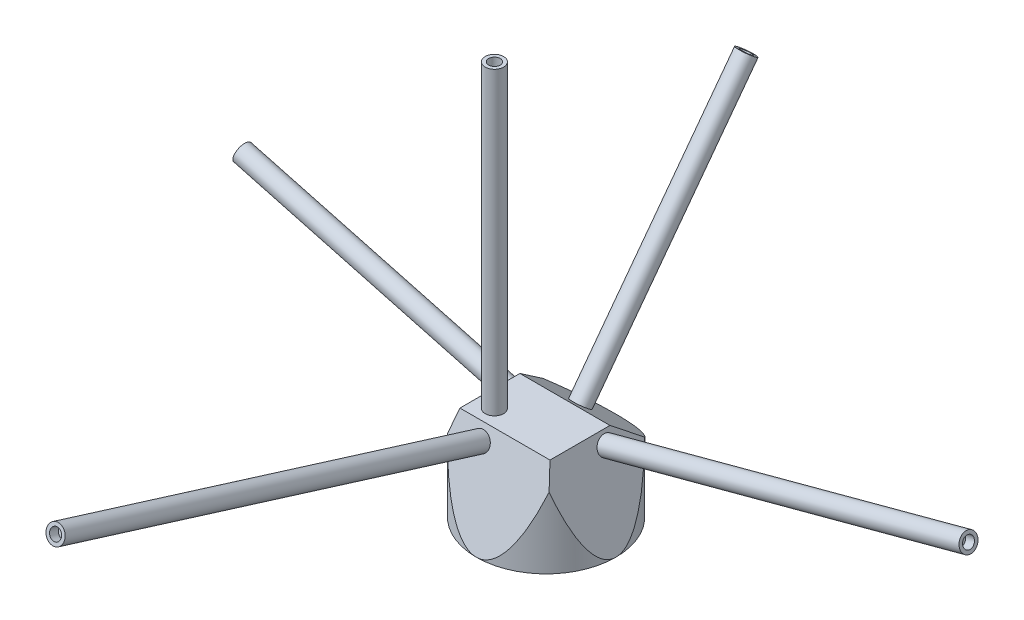
SolidWorks part; units mm, degrees
material "Ductile Iron"
ref_plane "Front Plane" through (0, 0, 0) normal (0, 0, 1) x (1, 0, 0)
ref_plane "Top Plane" through (0, 0, 0) normal (0, 1, 0) x (1, 0, 0)
ref_plane "Right Plane" through (0, 0, 0) normal (1, 0, 0) x (0, 0, -1)
sketch "Sketch1" plane through (0, 0, 0) normal (0, 1, 0) x (1, 0, 0)
  circle A0 centre (0, 0) radius 15.115
  dimension "D1" = 30.23
extrude "Boss-Extrude1" add sketch "Sketch1" against normal blind 20
ref_plane "Plane1" through (15.115, 0, 0) normal (1, 0, 0) x (0, 0, -1)
sketch "Sketch3" plane through (15.115, 0, 0) normal (1, 0, 0) x (0, 0, -1)
  line L0 (-8.9054, 0) -> (-15.115, -20)
  line L1 (15.115, 0) -> (-15.115, 0) construction
  line L2 (4.0746, 0) -> (15.115, -8.2598)
  line L3 (15.115, -20) -> (15.115, 0) construction
  line L4 (-15.115, 0) -> (-8.9054, 0)
  line L5 (4.0746, 0) -> (15.115, 0)
  line L7 (-15.115, -20) -> (-15.115, 0)
  line L10 (15.115, 0) -> (15.115, -8.2598)
  dimension "D1" = 4.0746
  dimension "D2" = 8.9054
  dimension "D3" = 8.2598
extrude "Cut-Extrude1" cut sketch "Sketch3" against normal through all
ref_plane "Plane2" through (0, 0, 15.115) normal (0, 0, 1) x (1, 0, 0)
sketch "Sketch7" plane through (0, 0, 15.115) normal (0, 0, 1) x (1, 0, 0)
  line L0 (15.115, 0) -> (9.75, 0)
  line L1 (12.213, 0) -> (-12.213, 0) construction
  line L2 (9.75, 0) -> (15.115, -20)
  line L3 (15.115, -20) -> (15.115, 0)
  line L4 (0, 1.9053) -> (0, -21.0091) construction
  line L5 (-15.115, -20) -> (-15.115, 0)
  line L6 (-9.75, 0) -> (-15.115, -20)
  line L7 (-15.115, 0) -> (-9.75, 0)
  dimension "D1" = 9.75
extrude "Cut-Extrude3" cut sketch "Sketch7" against normal through all
sketch "Sketch8" plane through (0, 0, 0) normal (0, 1, 0) x (1, 0, 0)
  line L0 (9.75, 4.0746) -> (9.75, -8.9054) construction
  line L1 (9.75, -8.9054) -> (-9.75, -8.9054) construction
  circle A0 centre (-5.954, -5.2387) radius 1.99
  dimension "D1" = 3.98
  dimension "D2" = 15.704
  dimension "D3" = 3.6667
extrude "Boss-Extrude2" add sketch "Sketch8" along normal blind 65
sketch "Sketch9" plane through (0, 65, 0) normal (0, 1, 0) x (1, 0, 0)
  circle A0 centre (-5.954, -5.2387) radius 1.25
  dimension "D1" = 2.5
extrude "Cut-Extrude4" cut sketch "Sketch9" against normal blind 2
sketch "Sketch11" plane through (0, 2.5218, 8.1224) normal (0, 0.2965, 0.955) x (1, 0, 0)
  line L0 (9.75, -2.6406) -> (-9.75, -2.6406) construction
  circle A0 centre (-4.3129, -5.8019) radius 1.99
  dimension "D1" = 3.98
  dimension "D2" = 6.6935
  dimension "D3" = 3.1613
extrude "Boss-Extrude3" add sketch "Sketch11" along normal blind 96.4
sketch "Sketch12" plane through (0, 31.106, 100.1871) normal (0, 0.2965, 0.955) x (1, 0, 0)
  circle A0 centre (-4.3129, -5.8019) radius 1.25
  dimension "D1" = 2.5
extrude "Cut-Extrude5" cut sketch "Sketch12" against normal blind 2
sketch "Sketch13" plane through (9.0955, 2.4399, 0) normal (0.9659, 0.2591, 0) x (0, 0, -1)
  line L0 (4.0746, -2.5261) -> (-8.9054, -2.5261) construction
  circle A0 centre (2.6311, -5.274) radius 1.99
  dimension "D1" = 3.98
  dimension "D2" = 1.4434
  dimension "D3" = 2.7479
extrude "Boss-Extrude4" add sketch "Sketch13" along normal blind 81.15
sketch "Sketch14" plane through (87.4745, 23.465, 0) normal (0.9659, 0.2591, 0) x (0, 0, -1)
  circle A0 centre (2.6311, -5.274) radius 1.25
  dimension "D1" = 2.5
extrude "Cut-Extrude6" cut sketch "Sketch14" against normal blind 2
sketch "Sketch15" plane through (-9.0955, 2.4399, 0) normal (-0.9659, 0.2591, 0) x (0, 0, 1)
  line L0 (-4.0746, -2.5261) -> (8.9054, -2.5261) construction
  circle A0 centre (-2.6311, -5.274) radius 1.99
  dimension "D1" = 3.98
  dimension "D2" = 1.4434
  dimension "D3" = 2.7479
extrude "Boss-Extrude5" add sketch "Sketch15" along normal blind 60
sketch "Sketch16" plane through (-67.0467, 17.9853, 0) normal (-0.9659, 0.2591, 0) x (0, 0, 1)
  circle A0 centre (-2.6311, -5.274) radius 1.25
  dimension "D1" = 2.5
extrude "Cut-Extrude7" cut sketch "Sketch16" against normal blind 2
sketch "Sketch17" plane through (0, 1.9544, -1.4622) normal (0, 0.8007, -0.599) x (1, 0, 0)
  line L0 (-9.75, 3.2626) -> (9.75, 3.2626) construction
  circle A0 centre (0, 7.4412) radius 1.99
  dimension "D1" = 3.98
  dimension "D2" = 11.0105
  dimension "D3" = 4.1786
extrude "Boss-Extrude6" add sketch "Sketch17" along normal blind 60
sketch "Sketch18" plane through (0, 49.9973, -37.4049) normal (0, 0.8007, -0.599) x (1, 0, 0)
  circle A0 centre (0, 7.4412) radius 1.25
  dimension "D1" = 2.5
extrude "Cut-Extrude8" cut sketch "Sketch18" against normal blind 2
